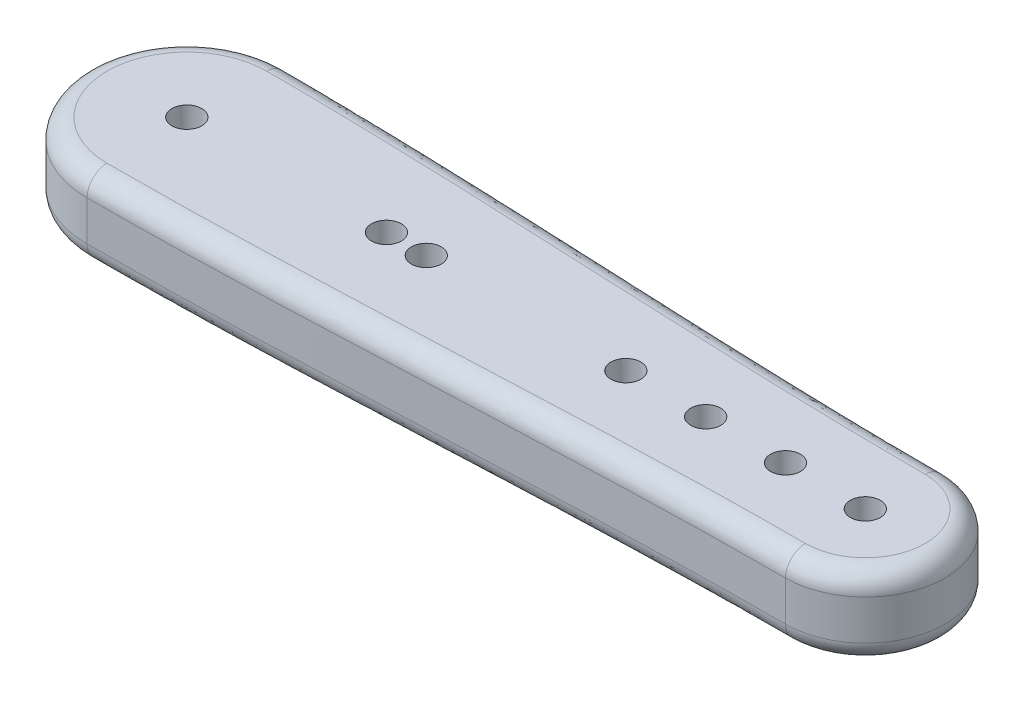
SolidWorks part; units mm, degrees
other "Markup1"
sketch "Sketch4" plane through (76, 8, 10.9958) normal (0.0273, 0.8989, 0.4374) x (0.9966, -0.0584, 0.0577)
ref_plane "Front Plane" through (0, 0, 0) normal (0, 0, 1) x (1, 0, 0)
ref_plane "Top Plane" through (0, 0, 0) normal (0, 1, 0) x (1, 0, 0)
ref_plane "Right Plane" through (0, 0, 0) normal (1, 0, 0) x (0, 0, -1)
sketch "Sketch2" plane through (0, 0, 0) normal (0, 1, 0) x (1, 0, 0)
  line L0 (0, 0) -> (68, 0) construction
  line L5 (27.2118, 10) -> (-27.2118, 10) construction
  line L6 (86.1569, 8) -> (49.8431, 8) construction
  line L7 (27.2118, -10) -> (-27.2118, -10) construction
  line L8 (86.1569, -8) -> (49.8431, -8) construction
  arc A0 (0, 10) -> (0, -10) centre (0, 0) ccw
  arc A1 (68, -8) -> (68, 8) centre (68, 0) ccw
  spline S0 degree 3 poles (0, 10) (22.6765, 10) (45.3039, 8) (68, 8) knots 0 0 0 0 1 1 1 1
  spline S1 degree 3 poles (0, -10) (22.6765, -10) (45.3039, -8) (68, -8) knots 0 0 0 0 1 1 1 1
  point P3 (21.8649, 0)
  dimension "D1" = 8
  dimension "D2" = 10
  dimension "D3" = 68
extrude "Boss-Extrude1" add sketch "Sketch2" along normal blind 8
sketch "Sketch3" plane through (0, 8, 0) normal (0, 1, 0) x (1, 0, 0)
  line L0 (0, 0) -> (68, 0) construction
  circle A0 centre (0, 0) radius 1.5
  circle A1 centre (68, 0) radius 1.5
  circle A2 centre (20, 0) radius 1.5
  circle A3 centre (24, 0) radius 1.5
  circle A4 centre (60, 0) radius 1.5
  circle A5 centre (52, 0) radius 1.5
  circle A6 centre (44, 0) radius 1.5
  dimension "D1" = 3
  dimension "D2" = 3
  dimension "D3" = 3
  dimension "D4" = 3
  dimension "D7" = 3
  dimension "D8" = 3
  dimension "D9" = 3
  dimension "D10" = 8
  dimension "D11" = 8
  dimension "D12" = 8
  dimension "D5" = 20
  dimension "D6" = 4
extrude "Cut-Extrude1" cut sketch "Sketch3" against normal blind 6.2
fillet "Fillet4" radius 2 4 edges at (76, 8, 0) (-10, 8, 0)
fillet "Fillet5" radius 2 4 edges at (76, 0, 0) (-10, 0, 0)
